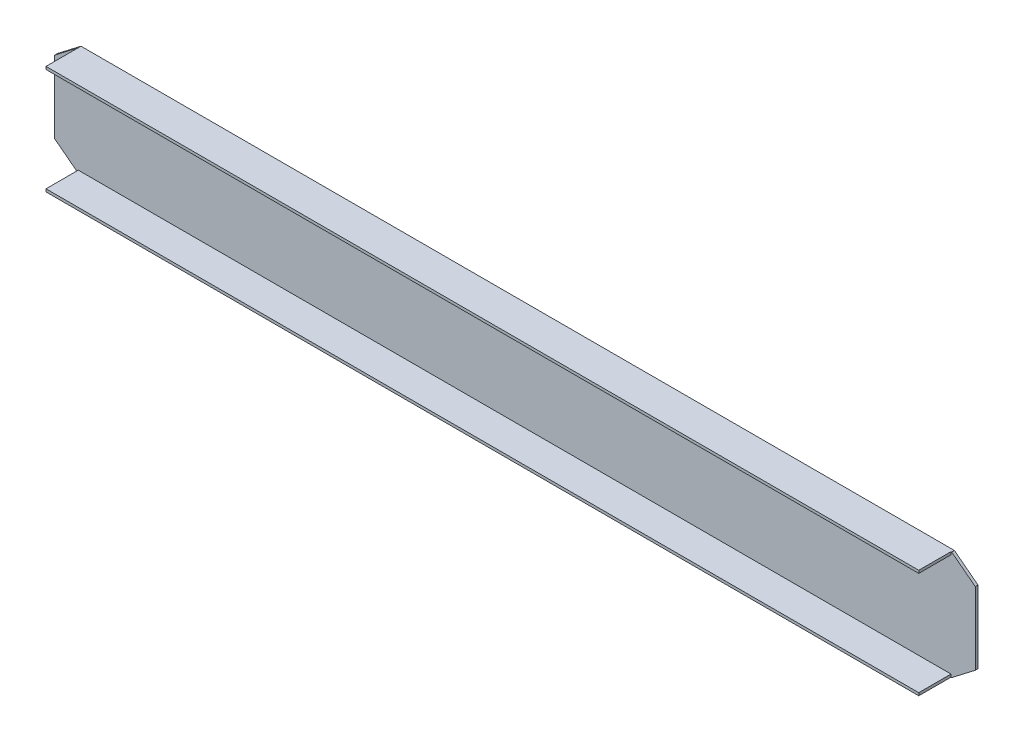
SolidWorks part; units mm, degrees
ref_plane "前视" through (0, 0, 0) normal (0, 0, 1) x (1, 0, 0)
ref_plane "上视" through (0, 0, 0) normal (0, 1, 0) x (1, 0, 0)
ref_plane "右视" through (0, 0, 0) normal (1, 0, 0) x (0, 0, -1)
sketch "草图1" plane through (0, 0, 0) normal (0, 0, 1) x (1, 0, 0)
  line L0 (0, -30.9807) -> (0, 402.9291) construction
  line L1 (-1205, 0) -> (1205, 0)
  line L2 (-1270, 50) -> (-1270, 250)
  line L3 (-1205, 300) -> (1205, 300)
  line L4 (-1270, 50) -> (-1205, 0)
  line L5 (-1270, 250) -> (-1205, 300)
  line L6 (-1329.5124, 150) -> (23.7415, 150) construction
  line L7 (-1307.9834, 230) -> (-31.6189, 230) construction
  line L8 (-1220, -101.4655) -> (-1220, 369.0978) construction
  line L9 (1270, 250) -> (1205, 300)
  line L10 (-1140, 369.0978) -> (-1140, -101.4655) construction
  line L11 (1270, 50) -> (1205, 0)
  line L12 (-1060, -101.4655) -> (-1060, 369.0978) construction
  line L13 (1270, 50) -> (1270, 250)
  line L14 (-980, 369.0978) -> (-980, -101.4655) construction
  point P8 (0, 300)
  point P65 (0, 0)
  dimension "D1" = 1205
  dimension "D2" = 300
  dimension "D3" = 65
  dimension "D4" = 65
  dimension "D5" = 50
  dimension "D6" = 50
  dimension "D7" = 70
  dimension "D8" = 80
  dimension "D9" = 50
  dimension "D10" = 80
  dimension "D11" = 80
  dimension "D12" = 80
extrude "基体-拉伸" add sketch "草图1" against normal blind 7.5
sketch "草图2" plane through (0, 0, 0) normal (0, 0, 1) x (1, 0, 0)
  line L0 (-1399.9508, 150) -> (-832.4876, 150) construction
  line L1 (-1205, 300) -> (1203.049, 300)
  line L2 (-1205, 300) -> (-1205, 292.5)
  line L3 (-1205, 292.5) -> (1203.049, 292.5)
  line L4 (1203.049, 300) -> (1203.049, 292.5)
  line L5 (-1205, 0) -> (1205, 0) construction
  line L6 (1203.049, 0) -> (1203.049, 7.5)
  line L7 (-1205, 7.5) -> (1203.049, 7.5)
  line L8 (-1205, 0) -> (-1205, 7.5)
  line L9 (-1205, 0) -> (1203.049, 0)
  dimension "D1" = 7.5
extrude "凸台-拉伸1" add sketch "草图2" along normal blind 89
sketch "草图3" plane through (0, 0, -7.5) normal (0, 0, -1) x (-1, 0, 0)
  line L0 (0, -46.5184) -> (0, 412.0245) construction
  line L1 (-180, 412.0245) -> (-180, -46.5184) construction
  line L2 (-580, 412.0245) -> (-580, -73.5011) construction
  line L3 (-1205, 300) -> (1205, 300) construction
  line L4 (-620, 270) -> (-540, 270)
  line L5 (-620, 270) -> (-620, 30)
  line L6 (-620, 30) -> (-540, 30)
  line L7 (-540, 270) -> (-540, 30)
  line L8 (-220, 270) -> (-140, 270)
  line L9 (-220, 270) -> (-220, 30)
  line L10 (-220, 30) -> (-140, 30)
  line L11 (-140, 270) -> (-140, 30)
  line L12 (140, 270) -> (140, 30)
  line L13 (220, 30) -> (140, 30)
  line L14 (220, 270) -> (220, 30)
  line L15 (220, 270) -> (140, 270)
  line L16 (540, 270) -> (540, 30)
  line L17 (620, 30) -> (540, 30)
  line L18 (620, 270) -> (620, 30)
  line L19 (620, 270) -> (540, 270)
  dimension "D1" = 180
  dimension "D2" = 400
  dimension "D3" = 240
  dimension "D4" = 30
  dimension "D5" = 80
  dimension "D6" = 80
extrude "凸台-拉伸2" add sketch "草图3" along normal blind 16
